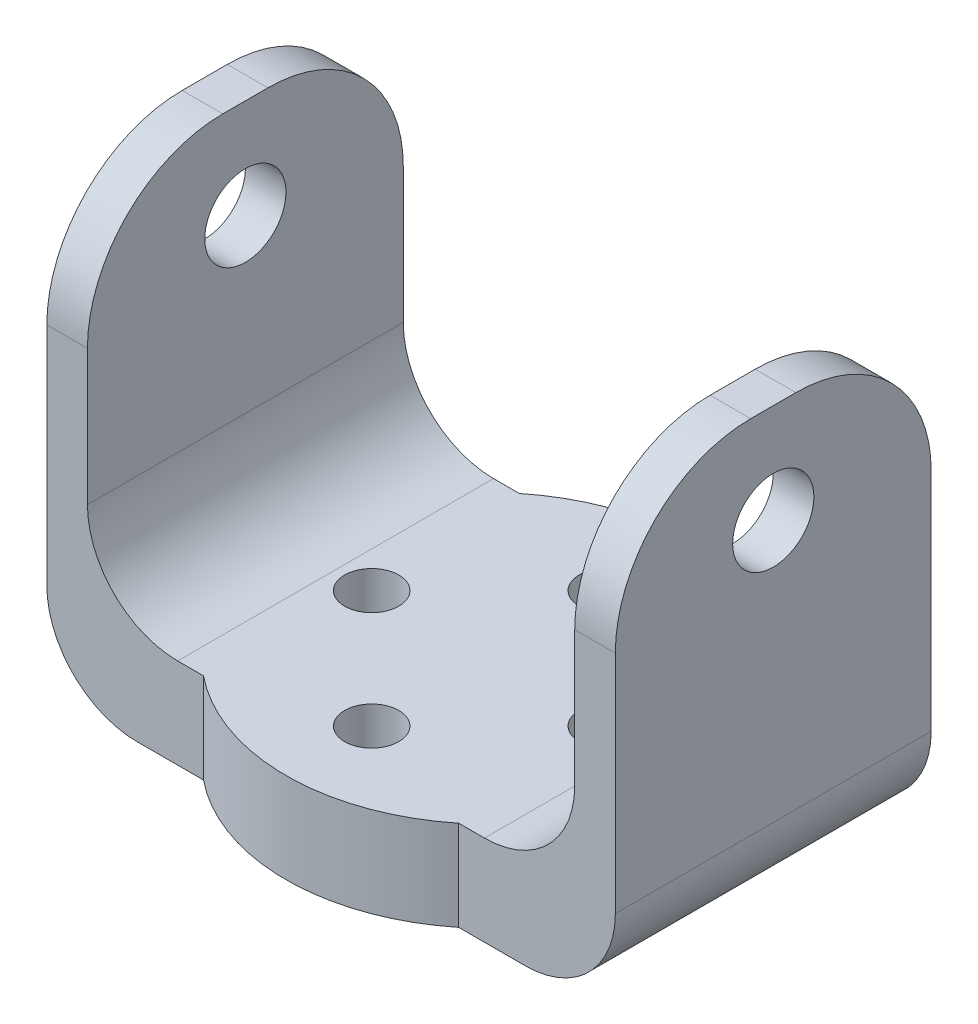
SolidWorks part; units mm, degrees
ref_plane "Front Plane" through (0, 0, 0) normal (0, 0, 1) x (1, 0, 0)
ref_plane "Top Plane" through (0, 0, 0) normal (0, 1, 0) x (1, 0, 0)
ref_plane "Right Plane" through (0, 0, 0) normal (1, 0, 0) x (0, 0, -1)
sketch "Sketch1" plane through (0, 0, 0) normal (0, 0, 1) x (1, 0, 0)
  line L0 (-31.5, 0) -> (31.5, 0)
  line L1 (31.5, 0) -> (31.5, 50)
  line L2 (31.5, 50) -> (27, 50)
  line L3 (27, 50) -> (27, 10)
  line L4 (27, 10) -> (-27, 10)
  line L5 (-27, 10) -> (-27, 50)
  line L6 (-27, 50) -> (-31.5, 50)
  line L7 (-31.5, 50) -> (-31.5, 0)
  point P6 (0, 0)
  dimension "D1" = 54
  dimension "D2" = 40
  dimension "D3" = 50
  dimension "D4" = 4.5
extrude "Boss-Extrude1" add sketch "Sketch1" against normal mid plane 35
sketch "Sketch2" plane through (0, 0, 0) normal (0, -1, 0) x (1, 0, 0)
  circle A0 centre (0, 0) radius 22.5
  dimension "D1" = 45
fillet "Fillet3" radius 10 4 edges at (27, 10, 0) (31.5, 0, 0) (-31.5, 0, 0) (-27, 10, 0)
extrude "Boss-Extrude4" add sketch "Sketch2" against normal blind 10 contours A0
sketch "Sketch4" plane through (0, 0, 0) normal (0, -1, 0) x (1, 0, 0)
  circle A0 centre (0, 13) radius 3
  circle A1 centre (13, 0) radius 3
  circle A2 centre (0, -13) radius 3
  circle A3 centre (-13, 0) radius 3
  point P12 (0, 0)
  dimension "D1" = 6
  dimension "D3" = 4
  dimension "D2" = 13
extrude "Cut-Extrude2" cut sketch "Sketch4" against normal blind 10
fillet "Fillet6" radius 15 4 edges at (29.25, 50, 17.5) (29.25, 50, -17.5) (-29.25, 50, -17.5) (-29.25, 50, 17.5)
sketch "Sketch6" plane through (31.5, 0, 0) normal (1, 0, 0) x (0, 0, -1)
  line L2 (-17.5, 10) -> (17.5, 10) construction
  circle A0 centre (0, 39) radius 4.5
  point P2 (0, 0)
  point P5 (0, 0)
  dimension "D1" = 9
  dimension "D2" = 29
extrude "Cut-Extrude3" cut sketch "Sketch6" against normal through all
